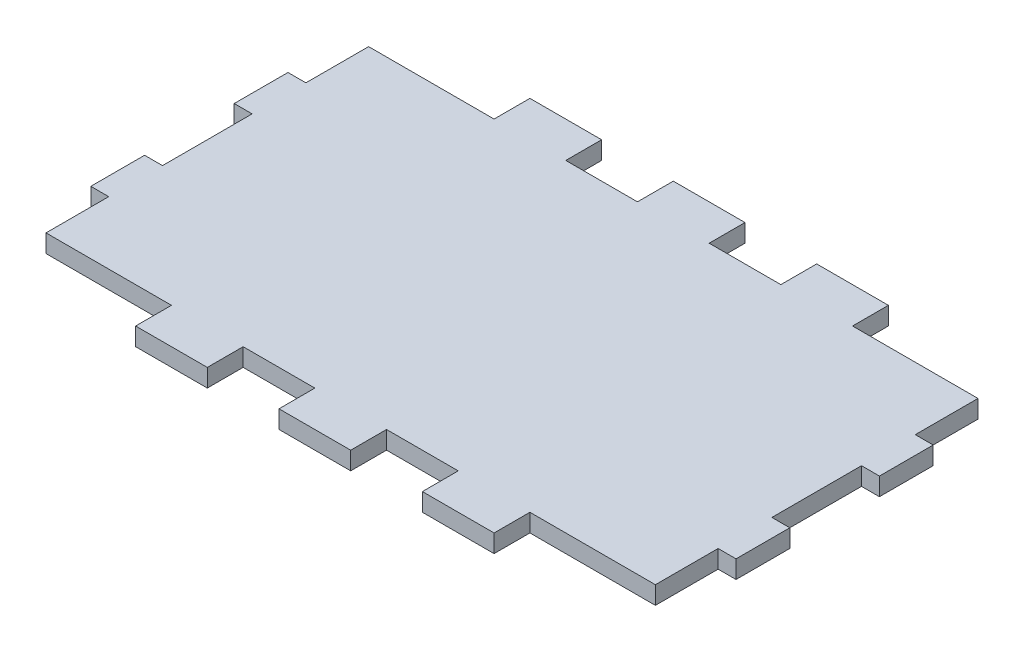
SolidWorks part; units mm, degrees
ref_plane "Plan de face" through (0, 0, 0) normal (0, 0, 1) x (1, 0, 0)
ref_plane "Plan de dessus" through (0, 0, 0) normal (0, 1, 0) x (1, 0, 0)
ref_plane "Plan de droite" through (0, 0, 0) normal (1, 0, 0) x (0, 0, -1)
sketch "Esquisse1" plane through (0, 0, 0) normal (0, 1, 0) x (1, 0, 0)
  line L1 (-90, 55) -> (90, 55)
  line L2 (-90, 55) -> (-90, -55)
  line L3 (-90, -55) -> (90, -55)
  line L4 (90, 55) -> (90, -55)
  line L5 (-90, 55) -> (90, -55) construction
  line L6 (-90, -55) -> (90, 55) construction
  point P0 (0, 0)
  dimension "D1" = 180
  dimension "D2" = 110
extrude "Boss.-Extru.1" add sketch "Esquisse1" along normal blind 5
sketch "Esquisse2" plane through (0, 5, 0) normal (0, 1, 0) x (1, 0, 0)
  line L0 (-90, -55) -> (90, -55) construction
  line L1 (-10, -55) -> (10, -55)
  line L2 (-10, -55) -> (-10, -45)
  line L3 (-10, -45) -> (10, -45)
  line L4 (10, -55) -> (10, -45)
  line L5 (90, 55) -> (-90, 55) construction
  line L6 (30, -55) -> (50, -55)
  line L7 (30, -55) -> (30, -45)
  line L8 (30, -45) -> (50, -45)
  line L9 (50, -55) -> (50, -45)
  line L10 (-50, -55) -> (-30, -55)
  line L11 (-50, -55) -> (-50, -45)
  line L12 (-50, -45) -> (-30, -45)
  line L13 (-30, -55) -> (-30, -45)
  line L14 (-50, 55) -> (-30, 55)
  line L15 (-50, 55) -> (-50, 45)
  line L16 (-50, 45) -> (-30, 45)
  line L17 (-30, 55) -> (-30, 45)
  line L18 (90, -55) -> (90, 55) construction
  line L19 (-10, 55) -> (10, 55)
  line L20 (-10, 55) -> (-10, 45)
  line L21 (-10, 45) -> (10, 45)
  line L22 (10, 55) -> (10, 45)
  line L23 (30, 55) -> (50, 55)
  line L24 (30, 55) -> (30, 45)
  line L25 (30, 45) -> (50, 45)
  line L26 (50, 55) -> (50, 45)
  line L27 (90, 27.5) -> (85, 27.5)
  line L28 (90, 27.5) -> (90, 12.5)
  line L29 (90, 12.5) -> (85, 12.5)
  line L30 (85, 27.5) -> (85, 12.5)
  line L31 (-90, 55) -> (-90, -55) construction
  line L32 (90, -27.5) -> (85, -27.5)
  line L33 (90, -27.5) -> (90, -12.5)
  line L34 (90, -12.5) -> (85, -12.5)
  line L35 (85, -27.5) -> (85, -12.5)
  line L36 (-90, 27.5) -> (-85, 27.5)
  line L37 (-90, 27.5) -> (-90, 12.5)
  line L38 (-90, 12.5) -> (-85, 12.5)
  line L39 (-85, 27.5) -> (-85, 12.5)
  line L40 (-85, 27.5) -> (-85, 45)
  line L41 (-90, -27.5) -> (-85, -27.5)
  line L42 (-90, -27.5) -> (-90, -12.5)
  line L43 (-90, -12.5) -> (-85, -12.5)
  line L44 (-85, -27.5) -> (-85, -12.5)
  line L45 (-85, 45) -> (-50, 45)
  line L46 (-30, 45) -> (-10, 45)
  line L47 (10, 45) -> (30, 45)
  line L48 (50, 45) -> (85, 45)
  line L49 (85, 45) -> (85, 27.5)
  line L50 (85, 12.5) -> (85, -12.5)
  line L51 (85, -27.5) -> (85, -45)
  line L52 (85, -45) -> (50, -45)
  line L53 (30, -45) -> (10, -45)
  line L54 (-10, -45) -> (-30, -45)
  line L55 (-50, -45) -> (-85, -45)
  line L56 (-85, -45) -> (-85, -27.5)
  line L57 (-85, 12.5) -> (-85, -12.5)
  point P48 (0, 45)
  line M38 (90, -55) -> (90, 55)
  line M39 (90, 55) -> (-90, 55)
  line M40 (-90, 55) -> (-90, -55)
  line M41 (-90, -55) -> (90, -55)
  dimension "D1" = 10
  dimension "D2" = 10
  dimension "D3" = 5
  dimension "D4" = 5
  dimension "D5" = 20
  dimension "D6" = 20
  dimension "D7" = 20
  dimension "D8" = 20
  dimension "D9" = 20
  dimension "D10" = 15
  dimension "D11" = 15
  dimension "D12" = 25
  dimension "D13" = 27.5
extrude "Enlèv. mat.-Extru.1" cut sketch "Esquisse2" against normal blind 5 contours L40 L45 L15 L36 M39 M40 | L48 L49 L27 L26 M38 M39 | L22 L47 L24 M39 | L17 L46 L20 M39 | L57 L38 L43 M40 | L55 L56 L41 L11 M40 M41 | L51 L52 L9 L32 M41 M38 | L29 L50 L34 M38 | L7 L53 L4 M41 | L2 L54 L13 M41
